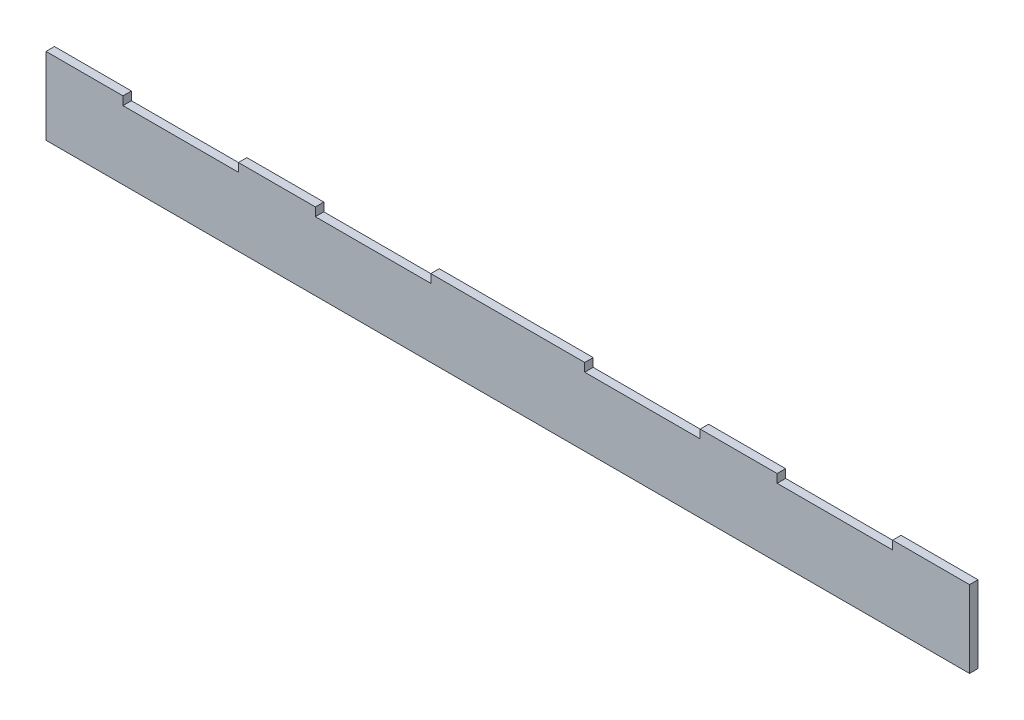
SolidWorks part; units mm, degrees
ref_plane "Front Plane" through (0, 0, 0) normal (0, 0, 1) x (1, 0, 0)
ref_plane "Top Plane" through (0, 0, 0) normal (0, 1, 0) x (1, 0, 0)
ref_plane "Right Plane" through (0, 0, 0) normal (1, 0, 0) x (0, 0, -1)
sketch "Sketch1" plane through (0, 0, 0) normal (0, 0, 1) x (1, 0, 0)
  line L0 (146.5558, -32.5929) -> (146.5558, 18.2071) construction
  line L1 (-158.2442, 18.2071) -> (-107.4442, 18.2071)
  line L2 (-158.2442, 18.2071) -> (-158.2442, -32.5929)
  line L3 (-158.2442, -32.5929) -> (451.3558, -32.5929)
  line L4 (451.3558, 18.2071) -> (451.3558, -32.5929)
  line L5 (-31.2442, 18.2071) -> (19.5558, 18.2071)
  line L6 (324.3558, 18.2071) -> (324.3558, 12.6191)
  line L7 (324.3558, 12.6191) -> (400.5558, 12.6191)
  line L8 (400.5558, 18.2071) -> (400.5558, 12.6191)
  line L9 (95.7558, 18.2071) -> (197.3558, 18.2071)
  line L10 (197.3558, 18.2071) -> (197.3558, 12.6191)
  line L11 (197.3558, 12.6191) -> (273.5558, 12.6191)
  line L12 (273.5558, 18.2071) -> (273.5558, 12.6191)
  line L13 (-107.4442, 18.2071) -> (-107.4442, 12.6191)
  line L14 (-31.2442, 12.6191) -> (-107.4442, 12.6191)
  line L15 (-31.2442, 18.2071) -> (-31.2442, 12.6191)
  line L16 (19.5558, 18.2071) -> (19.5558, 12.6191)
  line L17 (95.7558, 12.6191) -> (19.5558, 12.6191)
  line L18 (95.7558, 18.2071) -> (95.7558, 12.6191)
  line L19 (273.5558, 18.2071) -> (324.3558, 18.2071)
  line L20 (400.5558, 18.2071) -> (451.3558, 18.2071)
  dimension "D1" = 50.8
  dimension "D2" = 609.6
  dimension "D3" = 50.8
  dimension "D4" = 50.8
  dimension "D5" = 76.2
  dimension "D6" = 5.588
extrude "Boss-Extrude2" add sketch "Sketch1" along normal blind 5.588
equation "\"width\"= 9in"
equation "\"Height\"= 18in"
equation "\"thick\"= 0.22"
equation "\"D6@Sketch1\"=\"thick\""
equation "\"D1@Boss-Extrude2\"=\"thick\""
